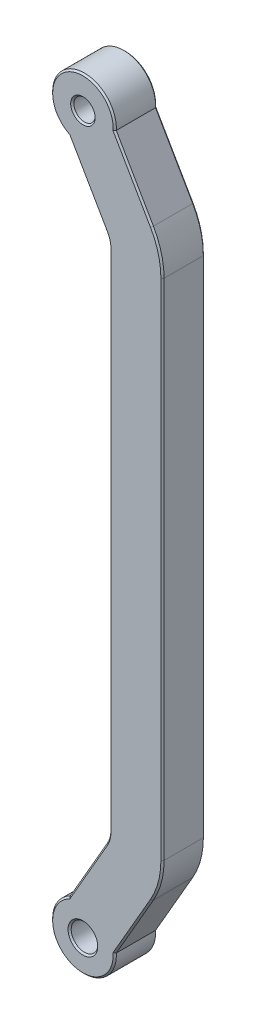
SolidWorks part; units mm, degrees
material "POM 乙缩醛共聚物"
ref_plane "前视基准面" through (0, 0, 0) normal (0, 0, 1) x (1, 0, 0)
ref_plane "上视基准面" through (0, 0, 0) normal (0, 1, 0) x (1, 0, 0)
ref_plane "右视基准面" through (0, 0, 0) normal (1, 0, 0) x (0, 0, -1)
sketch "草图1" plane through (0, 0, 0) normal (0, 0, 1) x (1, 0, 0)
  line L0 (0, 0) -> (0, 135) construction
  circle A0 centre (0, 0) radius 6
  circle A1 centre (0, 135) radius 6
  dimension "D2" = 12
  dimension "D1" = 135
extrude "凸台-拉伸1" add sketch "草图1" along normal blind 8
sketch "草图2" plane through (0, 0, 0) normal (0, 0, 1) x (1, 0, 0)
  line L0 (0, 135) -> (0, 0) construction
  line L1 (0, 0) -> (10, 17.3205)
  line L2 (10, 17.3205) -> (10, 117.6795)
  line L3 (10, 117.6795) -> (0, 135)
  line L4 (0, 67.5) -> (10, 67.5) construction
  dimension "D1" = 10
  dimension "D2" = 30
extrude "拉伸-薄壁1" add sketch "草图2" along normal up to surface (8 mm away) thin up to face at (6, 0, 8) thin type mid plane wall 10
sketch "草图3" plane through (0, 0, 8) normal (0, 0, 1) x (1, 0, 0)
  circle A1 centre (0, 0) radius 2.5
  dimension "D1" = 5
extrude "切除-拉伸1" cut sketch "草图3" against normal through all
sketch "草图4" plane through (0, 0, 0) normal (0, 0, -1) x (-1, 0, 0)
  circle A0 centre (0, 135) radius 2
  dimension "D1" = 4
extrude "切除-拉伸2" cut sketch "草图4" against normal through all
sketch "草图5" plane through (0, 0, 0) normal (0, 0, -1) x (-1, 0, 0)
  circle A0 centre (0, 135) radius 4
  dimension "D1" = 8
extrude "切除-拉伸3" cut sketch "草图5" against normal blind 4.5
chamfer "倒角1" distance 0.3 angle 45 28 edges at (4.8296, 116.2941, 8) (4.8296, 116.2941, 0) (5, 67.5, 8) (5, 67.5, 0) (4.8296, 18.7059, 8) (4.8296, 18.7059, 0) (0.8292, 11.4361, 8) (0.8292, 11.4361, 0) (-3, -5.1962, 8) (-3, -5.1962, 0) (9.4894, 6.4361, 8) (9.4894, 6.4361, 0) (14.4889, 16.1177, 8) (14.4889, 16.1177, 0) (15, 67.5, 8) (15, 67.5, 0) (14.4889, 118.8823, 8) (14.4889, 118.8823, 0) (9.4894, 128.5639, 8) (9.4894, 128.5639, 0) (-3, 140.1962, 8) (-3, 140.1962, 0) (0.8292, 123.5639, 8) (0.8292, 123.5639, 0) (2.5, 0, 0) (2.5, 0, 8) (-4, 135, 0) (-2, 135, 8)
